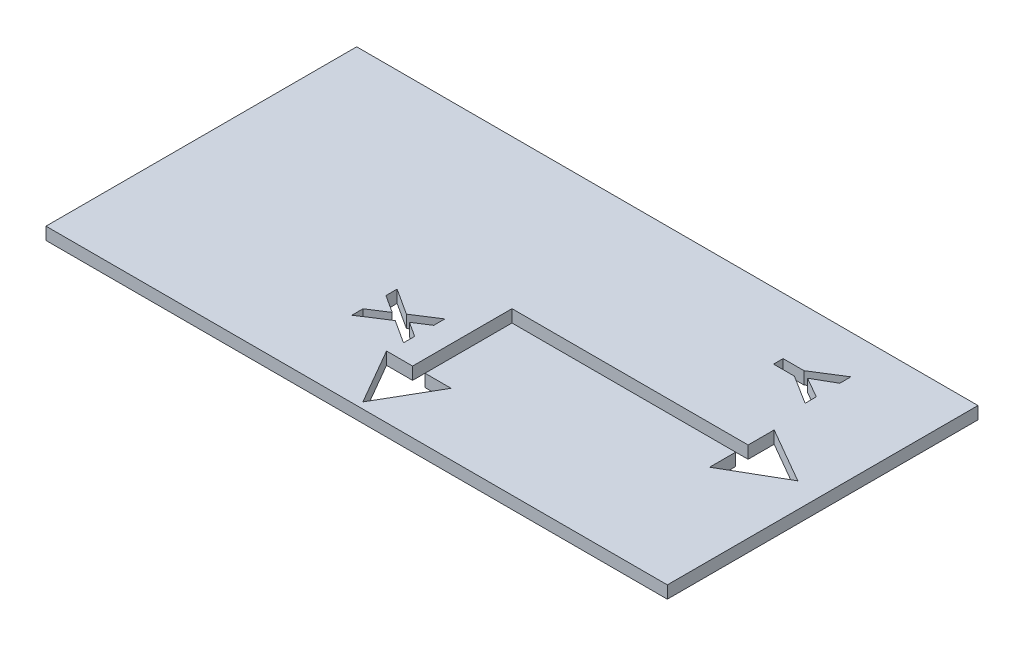
SolidWorks part; units mm, degrees
ref_plane "Спереди" through (0, 0, 0) normal (0, 0, 1) x (1, 0, 0)
ref_plane "Сверху" through (0, 0, 0) normal (0, 1, 0) x (1, 0, 0)
ref_plane "Справа" through (0, 0, 0) normal (1, 0, 0) x (0, 0, -1)
sketch "Эскиз2" plane through (0, 0, 0) normal (0, 0, 1) x (1, 0, 0)
  line L1 (-12.5, 25) -> (12.5, 25)
  line L2 (-12.5, 25) -> (-12.5, -25)
  line L3 (-12.5, -25) -> (12.5, -25)
  line L4 (12.5, 25) -> (12.5, -25)
  line L5 (-12.5, 25) -> (12.5, -25) construction
  line L6 (-12.5, -25) -> (12.5, 25) construction
  point P0 (0, 0)
  dimension "D1" = 50
  dimension "D2" = 25
extrude "Бобышка-Вытянуть2" add sketch "Эскиз2" along normal blind 1 contours L2 L1 L4 L3
sketch "Эскиз6" plane through (0, 0, 1) normal (0, 0, 1) x (1, 0, 0)
  line L0 (0, 25) -> (0, -25) construction
  line L1 (-12.5, 25) -> (12.5, 25) construction
  line L2 (-12.5, -25) -> (12.5, -25) construction
  line L3 (-12.5, 0) -> (12.5, 0) construction
  line L4 (12.5, 25) -> (12.5, -25) construction
  line L6 (0.5, 20) -> (-0.5, 20) construction
  line L7 (0.5, 20) -> (0.5, -20) construction
  line L8 (0.5, -20) -> (-0.5, -20) construction
  line L9 (-0.5, 20) -> (-0.5, -20) construction
  line L10 (0.5, 20) -> (-0.5, -20) construction
  line L11 (0.5, -20) -> (-0.5, 20) construction
  line L12 (-9, 0.5) -> (9, 0.5) construction
  line L13 (-9, 0.5) -> (-9, -0.5) construction
  line L14 (-9, -0.5) -> (9, -0.5) construction
  line L15 (9, 0.5) -> (9, -0.5) construction
  line L16 (-9, 0.5) -> (9, -0.5) construction
  line L17 (-9, -0.5) -> (9, 0.5) construction
  line L18 (12, 0) -> (7.5, 2.5981)
  line L19 (7.5, 2.5981) -> (7.5, -2.5981)
  line L20 (7.5, -2.5981) -> (12, 0)
  line L21 (0, 23) -> (-2.5981, 18.5)
  line L22 (-2.5981, 18.5) -> (2.5981, 18.5)
  line L23 (2.5981, 18.5) -> (0, 23)
  line L26 (-0.5, -0.5) -> (7.5, -0.5)
  line L27 (7.5, 0.5) -> (7.5, -0.5)
  line L28 (-7.5, 0.5) -> (7.5, -0.5) construction
  line L29 (-7.5, -0.5) -> (7.5, 0.5) construction
  line L30 (0.5, -18.5) -> (-0.5, -18.5)
  line L32 (0.5, 18.5) -> (-0.5, 18.5)
  line L33 (-0.5, -0.5) -> (-0.5, 18.5)
  line L34 (0.5, -18.5) -> (-0.5, 18.5) construction
  line L35 (0.5, 18.5) -> (-0.5, -18.5) construction
  line L37 (0.5, 0.5) -> (7.5, 0.5)
  line L38 (0.5, 0.5) -> (0.5, 18.5)
  circle A0 centre (9, 0) radius 1.5 construction
  circle A1 centre (0, 20) radius 1.5 construction
  point P2 (0, 0)
  point P5 (0, 25)
  point P9 (0, -25)
  point P15 (0, 0)
  point P18 (0, 0)
  point P29 (0, 0)
  point P38 (0, 0)
  dimension "D5" = 3
  dimension "D1" = 40
  dimension "D2" = 1
  dimension "D3" = 18
  dimension "D4" = 1
extrude "Вырез-Вытянуть3" cut sketch "Эскиз6" against normal blind 8 contours L22 L23 L21 | L37 L38 L22 L33 L26 L19 | L19 L20 L18
sketch "Эскиз7" plane through (0, 0, 1) normal (0, 0, 1) x (1, 0, 0)
  line L0 (-9.3635, 13.889) -> (-3.6514, 13.889) construction
  line L1 (-3.6514, 13.889) -> (2.7339, -6.4854) construction
  line L2 (2.7339, -6.4854) -> (10.4494, -6.4854) construction
  text T0 "<b>Y</b>"
  text T1 "<b>X</b>"
extrude "Бобышка-Вытянуть4" add sketch "Эскиз7" against normal blind 16 separate body
combine bodies "Соединить1" operation type subtract main body 113 bodies to subtract 114 115
move or copy body "Тело-Переместить/Копировать1" bodies to move or copy 116 copy no rotation origin (-0.1667, -0.1667, 0.3333) rotation axis (-0.5774, -0.5774, -0.5774) rotation angle 120
scale "Масштаб1" scale about origin uniform scaling yes scale factor 0.02
